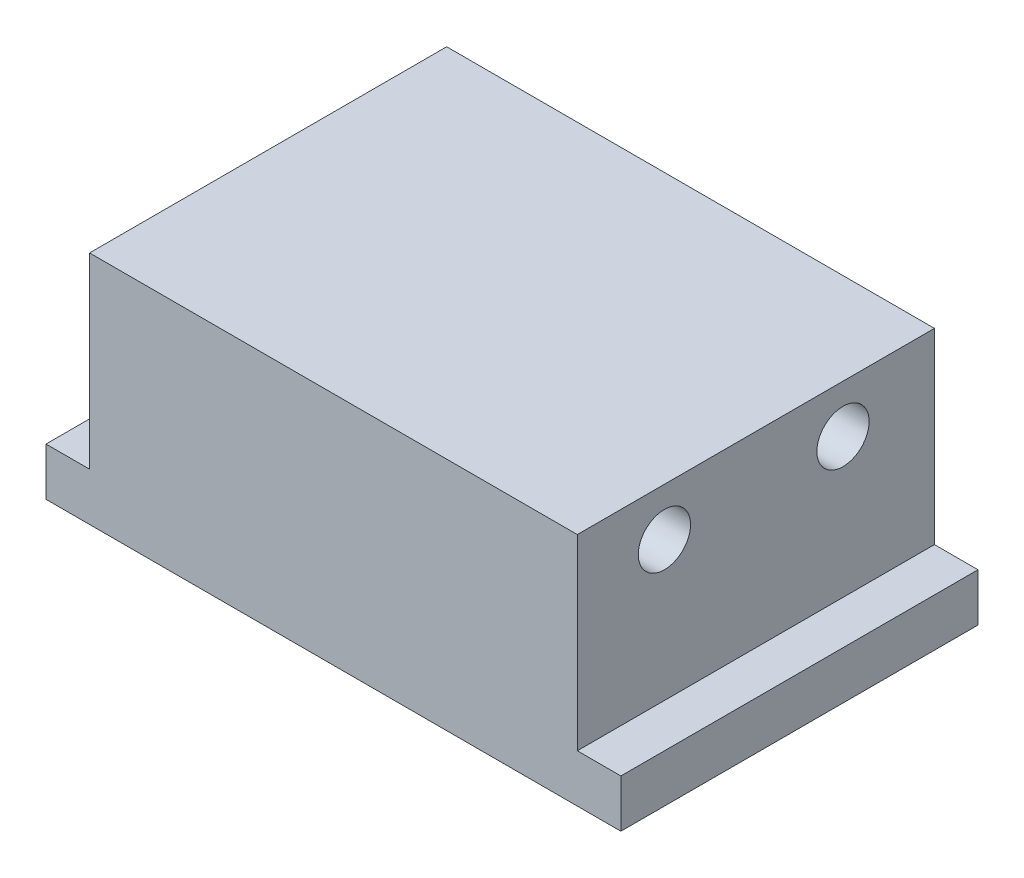
SolidWorks part; units mm, degrees
ref_plane "Front Plane" through (0, 0, 0) normal (0, 0, 1) x (1, 0, 0)
ref_plane "Top Plane" through (0, 0, 0) normal (0, 1, 0) x (1, 0, 0)
ref_plane "Right Plane" through (0, 0, 0) normal (1, 0, 0) x (0, 0, -1)
sketch "Sketch1" plane through (0, 0, 0) normal (0, 1, 0) x (1, 0, 0)
  line L1 (-114.8722, 48.5859) -> (17.1278, 48.5859)
  line L2 (-114.8722, 48.5859) -> (-114.8722, -33.4141)
  line L3 (-114.8722, -33.4141) -> (17.1278, -33.4141)
  line L4 (17.1278, 48.5859) -> (17.1278, -33.4141)
  dimension "D1" = 82
  dimension "D2" = 132
extrude "Boss-Extrude1" add sketch "Sketch1" along normal blind 11
sketch "Sketch2" plane through (0, 11, 0) normal (0, 1, 0) x (1, 0, 0)
  line L0 (17.1278, 48.5859) -> (-114.8722, 48.5859) construction
  line L1 (-104.8722, 48.5859) -> (7.1278, 48.5859)
  line L2 (-104.8722, 48.5859) -> (-104.8722, -33.4141)
  line L3 (-104.8722, -33.4141) -> (7.1278, -33.4141)
  line L4 (7.1278, 48.5859) -> (7.1278, -33.4141)
  line L5 (-114.8722, -33.4141) -> (17.1278, -33.4141) construction
  line L6 (-114.8722, 48.5859) -> (-114.8722, -33.4141) construction
  line L7 (17.1278, -33.4141) -> (17.1278, 48.5859) construction
  dimension "D1" = 10
  dimension "D2" = 10
extrude "Boss-Extrude2" add sketch "Sketch2" along normal blind 43
sketch "Sketch3" plane through (7.1278, 0, 0) normal (1, 0, 0) x (0, 0, -1)
  line L0 (-33.4141, 54) -> (48.5859, 54) construction
  line L1 (-33.4141, 54) -> (-33.4141, 11) construction
  circle A0 centre (-13.4141, 43) radius 6
  circle A1 centre (27.5859, 43) radius 6
  dimension "D3" = 12
  dimension "D1" = 11
  dimension "D2" = 20
  dimension "D4" = 41
  dimension "D5" = 0
extrude "Cut-Extrude1" cut sketch "Sketch3" against normal up to surface (112 mm away) up to face at (-104.8722, 32.5, -7.5859)
scale "Scale1" scale about centroid uniform scaling yes scale factor 0.1
